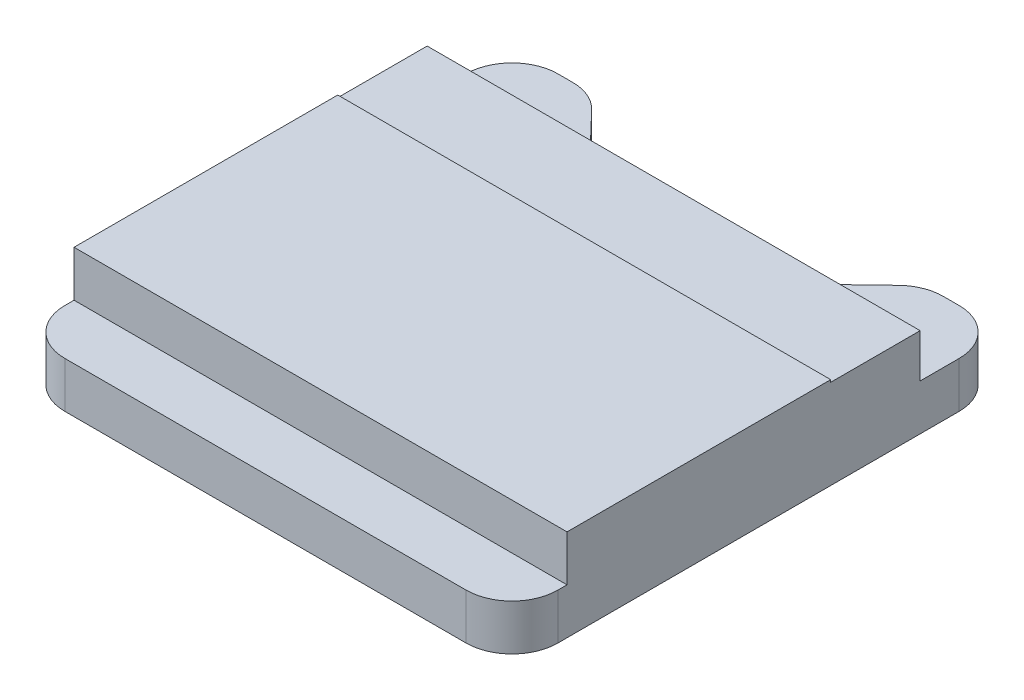
SolidWorks part; units mm, degrees
ref_plane "Front Plane" through (0, 0, 0) normal (0, 0, 1) x (1, 0, 0)
ref_plane "Top Plane" through (0, 0, 0) normal (0, 1, 0) x (1, 0, 0)
ref_plane "Right Plane" through (0, 0, 0) normal (1, 0, 0) x (0, 0, -1)
sketch "Sketch1" plane through (0, 0, 0) normal (0, 1, 0) x (1, 0, 0)
  line L0 (-9.2075, 13.6525) -> (-6.1636, 10.4775)
  line L1 (-13.6525, -13.6525) -> (13.6525, -13.6525)
  line L2 (-13.6525, -13.6525) -> (-13.6525, 13.6525)
  line L3 (-13.6525, 13.6525) -> (13.6525, 13.6525)
  line L4 (13.6525, -13.6525) -> (13.6525, 13.6525)
  line L5 (-13.6525, -13.6525) -> (13.6525, 13.6525) construction
  line L6 (-13.6525, 13.6525) -> (13.6525, -13.6525) construction
  line L7 (-6.1636, 10.4775) -> (5.8958, 10.4775)
  line L8 (5.8958, 10.4775) -> (9.2075, 13.6525)
  point P0 (0, 0)
  dimension "D1" = 27.305
  dimension "D2" = 27.305
  dimension "D3" = 3.175
  dimension "D4" = 4.445
  dimension "D5" = 4.445
  dimension "D6" = 12.0594
extrude "Boss-Extrude1" add sketch "Sketch1" along normal blind 2.54 contours L8 L7 L0 L3 L2 L1 L4
fillet "Fillet1" radius 2.54 8 edges at (-13.6525, 1.27, -13.6525) (-9.2075, 1.27, -13.6525) (-6.1636, 1.27, -10.4775) (9.2075, 1.27, -13.6525) (5.8958, 1.27, -10.4775) (13.6525, 1.27, -13.6525) (13.6525, 1.27, 13.6525) (-13.6525, 1.27, 13.6525)
sketch "Sketch2" plane through (0, 2.54, 0) normal (0, 1, 0) x (1, 0, 0)
  line L0 (13.6525, -11.1125) -> (13.6525, 11.1125) construction
  line L1 (-13.6525, 8.9535) -> (13.6525, 8.9535)
  line L2 (-13.6525, 8.9535) -> (-13.6525, -10.6045)
  line L3 (-13.6525, -10.6045) -> (13.6525, -10.6045)
  line L4 (13.6525, 8.9535) -> (13.6525, -10.6045)
  line L5 (-13.6525, 8.9535) -> (13.6525, -10.6045) construction
  line L6 (-13.6525, -10.6045) -> (13.6525, 8.9535) construction
  line L7 (-11.1125, -13.6525) -> (11.1125, -13.6525) construction
  line L8 (-11.1125, 13.6525) -> (-10.2911, 13.6525) construction
  line L9 (-13.6525, -11.1125) -> (-13.6525, 11.1125) construction
  point P0 (0, -0.8255)
  point P9 (-10.7018, 13.6525)
  dimension "D1" = 3.048
  dimension "D2" = 4.699
extrude "Boss-Extrude2" add sketch "Sketch2" along normal blind 2.413
sketch "Sketch3" plane through (0, 4.953, 0) normal (0, 1, 0) x (1, 0, 0)
  line L0 (-13.6525, 8.9535) -> (-13.6525, -10.6045) construction
  line L1 (-13.6525, 4.0005) -> (13.6525, 4.0005)
  line L2 (-13.6525, 4.0005) -> (-13.6525, -10.6045)
  line L3 (-13.6525, -10.6045) -> (13.6525, -10.6045)
  line L4 (13.6525, 4.0005) -> (13.6525, -10.6045)
  line L5 (-13.6525, 4.0005) -> (13.6525, -10.6045) construction
  line L6 (-13.6525, -10.6045) -> (13.6525, 4.0005) construction
  point P0 (0, -3.302)
  dimension "D1" = 14.605
extrude "Boss-Extrude3" add sketch "Sketch3" along normal blind 0.127
sketch "Sketch4" plane through (0, 0, 0) normal (0, 1, 0) x (1, 0, 0)
  line L0 (0, 0) -> (0, 10.4775) construction
  line L3 (-5.08, 10.4775) -> (4.8749, 10.4775) construction
  line L4 (0, 10.4775) -> (0, -13.6525) construction
  line L5 (-11.1125, -13.6525) -> (11.1125, -13.6525) construction
